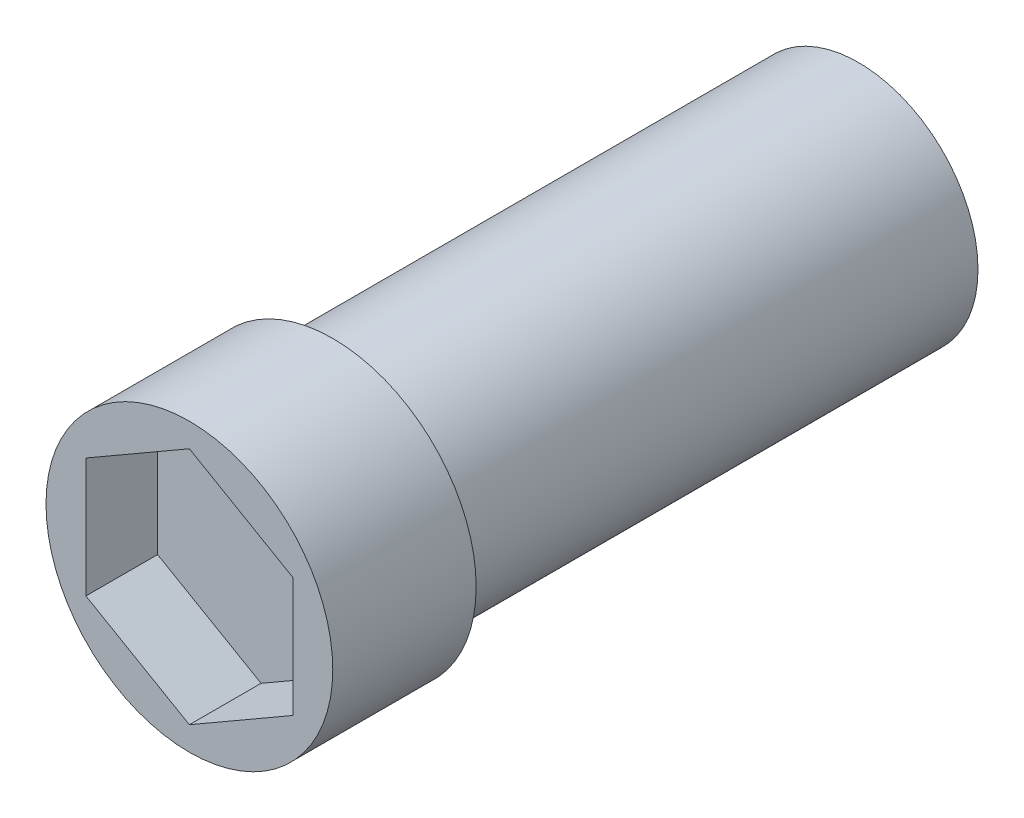
SolidWorks part; units mm, degrees
ref_plane "Front Plane" through (0, 0, 0) normal (0, 0, 1) x (1, 0, 0)
ref_plane "Top Plane" through (0, 0, 0) normal (0, 1, 0) x (1, 0, 0)
ref_plane "Right Plane" through (0, 0, 0) normal (1, 0, 0) x (0, 0, -1)
sketch "Sketch1" plane through (0, 0, 0) normal (0, 0, 1) x (1, 0, 0)
  circle A0 centre (0, 0) radius 2.5
  dimension "D1" = 5
extrude "Boss-Extrude1" add sketch "Sketch1" along normal blind 11
sketch "Sketch2" plane through (0, 0, 11) normal (0, 0, 1) x (1, 0, 0)
  circle A0 centre (0, 0) radius 3
  dimension "D1" = 6
extrude "Boss-Extrude2" add sketch "Sketch2" along normal blind 3 contours A0
sketch "Sketch3" plane through (0, 0, 14) normal (0, 0, 1) x (1, 0, 0)
  line L1 (0, 2.5) -> (-2.1651, 1.25)
  line L2 (-2.1651, 1.25) -> (-2.1651, -1.25)
  line L3 (-2.1651, -1.25) -> (0, -2.5)
  line L4 (0, -2.5) -> (2.1651, -1.25)
  line L5 (2.1651, -1.25) -> (2.1651, 1.25)
  line L6 (2.1651, 1.25) -> (0, 2.5)
  circle A0 centre (0, 0) radius 2.1651 construction
  dimension "D1" = 2.5
extrude "Cut-Extrude1" cut sketch "Sketch3" against normal blind 1.5 contours L6 L1 L2 L3 L4 L5
